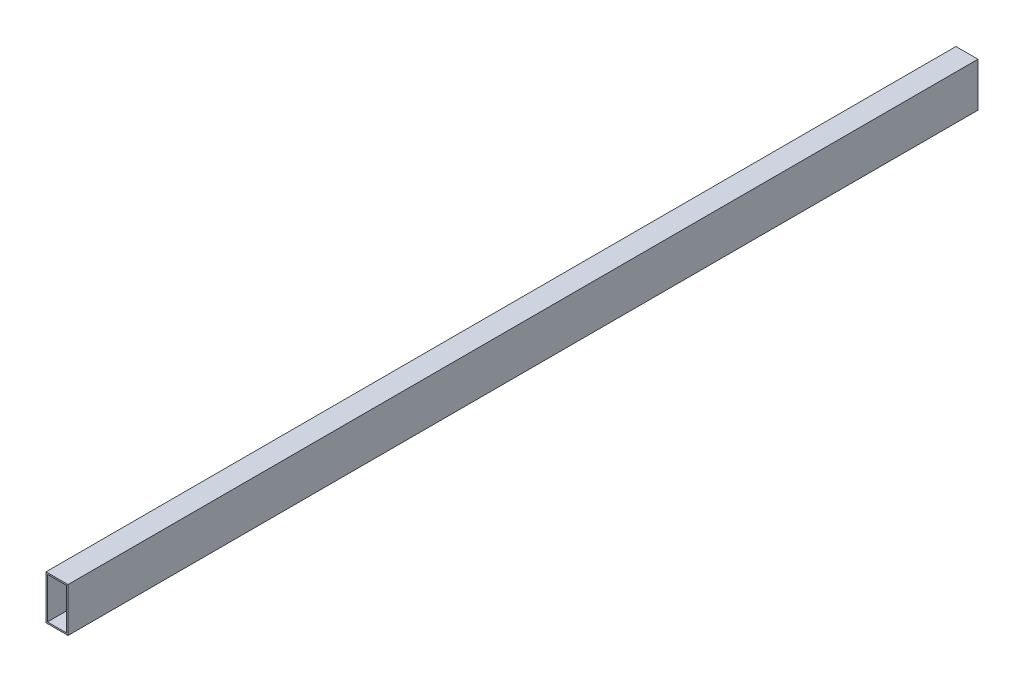
SolidWorks part; units mm, degrees
material "6061 Alloy"
ref_plane "Front Plane" through (0, 0, 0) normal (0, 0, 1) x (1, 0, 0)
ref_plane "Top Plane" through (0, 0, 0) normal (0, 1, 0) x (1, 0, 0)
ref_plane "Right Plane" through (0, 0, 0) normal (1, 0, 0) x (0, 0, -1)
sketch "Sketch1" plane through (0, 0, 0) normal (0, 0, 1) x (1, 0, 0)
  line L1 (-48.4372, -30.1994) -> (-23.0372, -30.1994)
  line L2 (-48.4372, -30.1994) -> (-48.4372, 20.6006)
  line L3 (-48.4372, 20.6006) -> (-23.0372, 20.6006)
  line L4 (-23.0372, -30.1994) -> (-23.0372, 20.6006)
  dimension "D1" = 25.4
  dimension "D2" = 50.8
extrude "Boss-Extrude1" add sketch "Sketch1" along normal blind 1047.75
sketch "Sketch2" plane through (0, 0, 1047.75) normal (0, 0, 1) x (1, 0, 0)
  line L0 (-48.4372, 20.6006) -> (-48.4372, -30.1994) construction
  line L1 (-46.7862, 18.9496) -> (-24.6882, 18.9496)
  line L2 (-46.7862, 18.9496) -> (-46.7862, -28.5484)
  line L3 (-46.7862, -28.5484) -> (-24.6882, -28.5484)
  line L4 (-24.6882, 18.9496) -> (-24.6882, -28.5484)
  line L5 (-46.7862, 18.9496) -> (-24.6882, -28.5484) construction
  line L6 (-46.7862, -28.5484) -> (-24.6882, 18.9496) construction
  line L7 (-23.0372, -30.1994) -> (-23.0372, 20.6006) construction
  line L8 (-23.0372, 20.6006) -> (-48.4372, 20.6006) construction
  line L9 (-48.4372, -30.1994) -> (-23.0372, -30.1994) construction
  point P0 (-35.7372, -4.7994)
  dimension "D1" = 1.651
  dimension "D2" = 1.651
  dimension "D3" = 1.651
  dimension "D4" = 1.651
extrude "Cut-Extrude1" cut sketch "Sketch2" against normal through all
